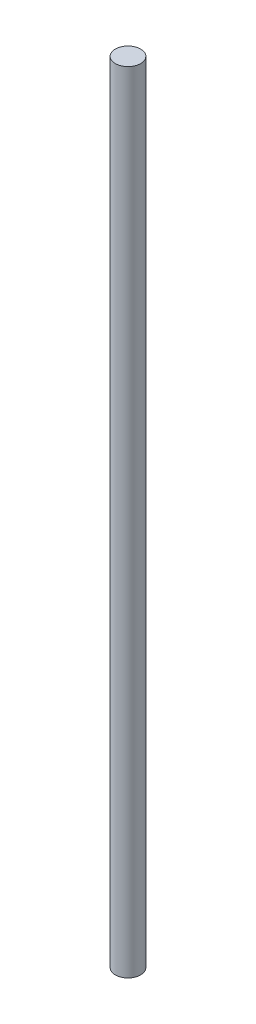
SolidWorks part; units mm, degrees
ref_plane "Plan de face" through (0, 0, 0) normal (0, 0, 1) x (1, 0, 0)
ref_plane "Plan de dessus" through (0, 0, 0) normal (0, 1, 0) x (1, 0, 0)
ref_plane "Plan de droite" through (0, 0, 0) normal (1, 0, 0) x (0, 0, -1)
sketch "Sketch1" plane through (0, 0, 0) normal (0, 1, 0) x (1, 0, 0)
  circle A0 centre (0, 0) radius 4
  dimension "D1" = 8
extrude "Boss-Extrude1" add sketch "Sketch1" along normal blind 250
